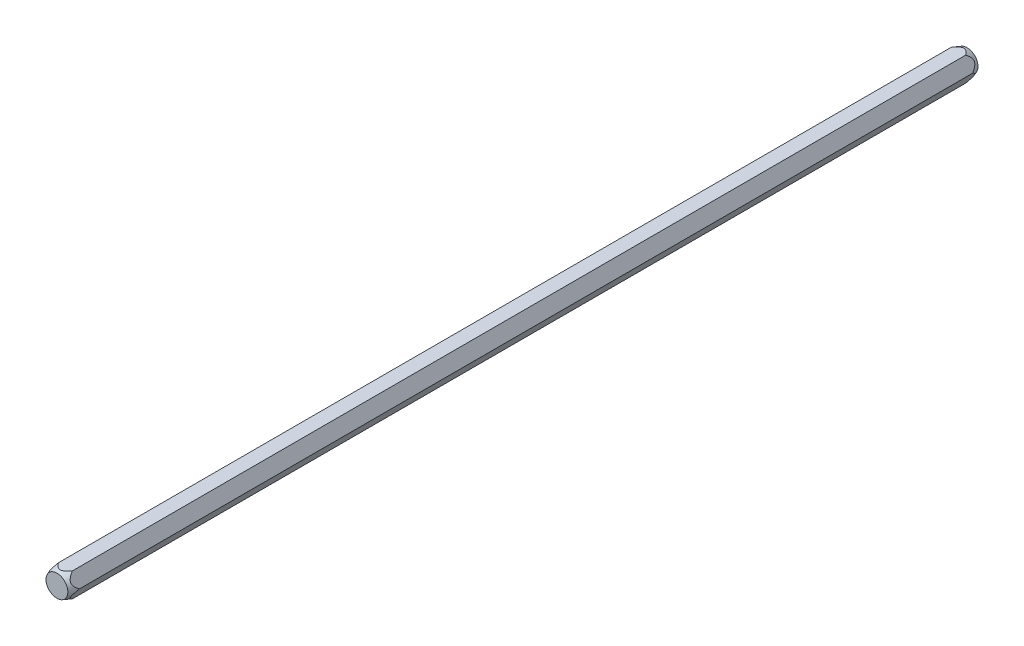
SolidWorks part; units mm, degrees
ref_plane "Alzado" through (0, 0, 0) normal (0, 0, 1) x (1, 0, 0)
ref_plane "Planta" through (0, 0, 0) normal (0, 1, 0) x (1, 0, 0)
ref_plane "Vista lateral" through (0, 0, 0) normal (1, 0, 0) x (0, 0, -1)
sketch "Croquis1" plane through (0, 0, 0) normal (0, 0, 1) x (1, 0, 0)
  line L0 (-2.3094, 0) -> (0, 0) construction
  line L1 (2.3094, 0) -> (1.1547, 2)
  line L2 (1.1547, 2) -> (-1.1547, 2)
  line L3 (-1.1547, 2) -> (-2.3094, 0)
  line L4 (-2.3094, 0) -> (-1.1547, -2)
  line L5 (-1.1547, -2) -> (1.1547, -2)
  line L6 (1.1547, -2) -> (2.3094, 0)
  circle A0 centre (0, 0) radius 2 construction
  dimension "D1" = 2
extrude "Saliente-Extruir1" add sketch "Croquis1" along normal blind 150
sketch "Croquis2" plane through (0, 0, 150) normal (0, 0, 1) x (1, 0, 0)
  circle A0 centre (0, 0) radius 1.8
  dimension "D1" = 3.6
extrude "Cortar-Extruir2" cut sketch "Croquis2" against normal blind 2 draft 20 flip side to cut
ref_plane "Plano1" through (0, 0, 75) normal (0, 0, 1) x (1, 0, 0)
mirror "Simetría1" about plane through (0, 0, 75) normal (0, 0, 1) of "Cortar-Extruir2"
